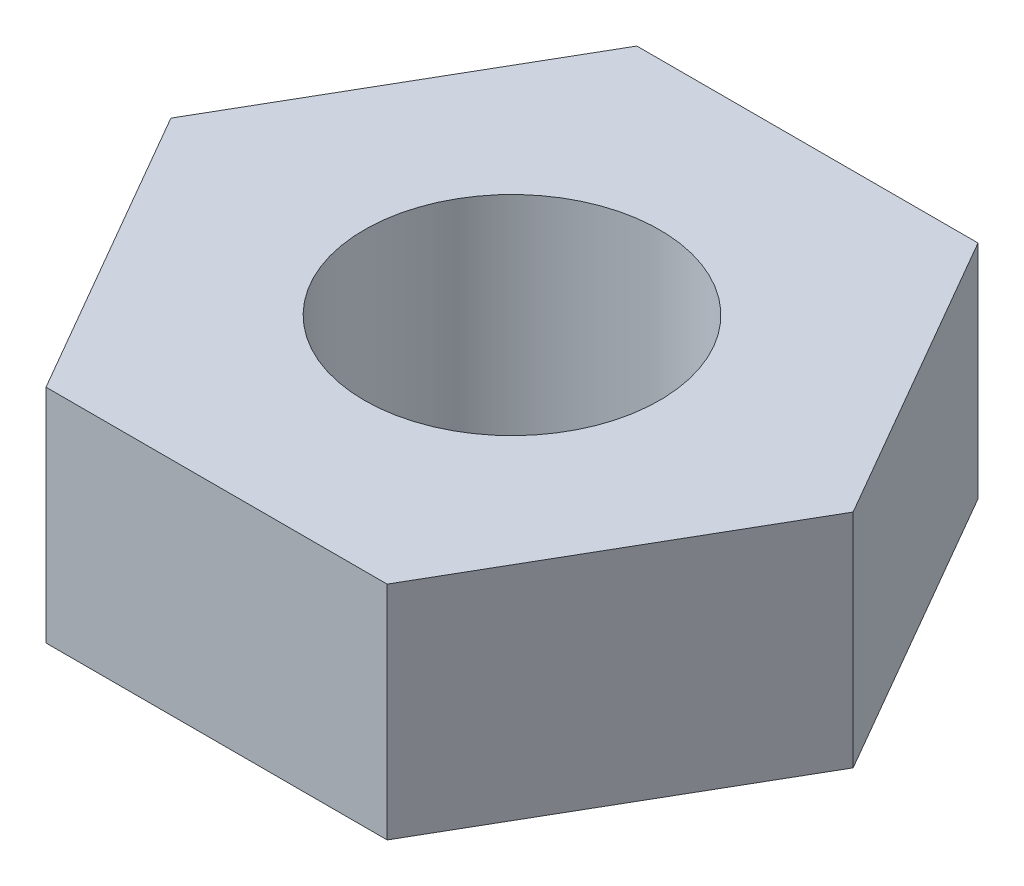
SolidWorks part; units mm, degrees
ref_plane "Front Plane" through (0, 0, 0) normal (0, 0, 1) x (1, 0, 0)
ref_plane "Top Plane" through (0, 0, 0) normal (0, 1, 0) x (1, 0, 0)
ref_plane "Right Plane" through (0, 0, 0) normal (1, 0, 0) x (0, 0, -1)
sketch "Sketch1" plane through (0, 0, 0) normal (0, 1, 0) x (1, 0, 0)
  line L1 (-4.6188, 0) -> (-2.3094, -4)
  line L2 (-2.3094, -4) -> (2.3094, -4)
  line L3 (2.3094, -4) -> (4.6188, 0)
  line L4 (4.6188, 0) -> (2.3094, 4)
  line L5 (2.3094, 4) -> (-2.3094, 4)
  line L6 (-2.3094, 4) -> (-4.6188, 0)
  circle A0 centre (0, 0) radius 4 construction
  circle A1 centre (0, 0) radius 2
  dimension "D1" = 8
  dimension "D2" = 4
extrude "Boss-Extrude1" add sketch "Sketch1" along normal blind 3
